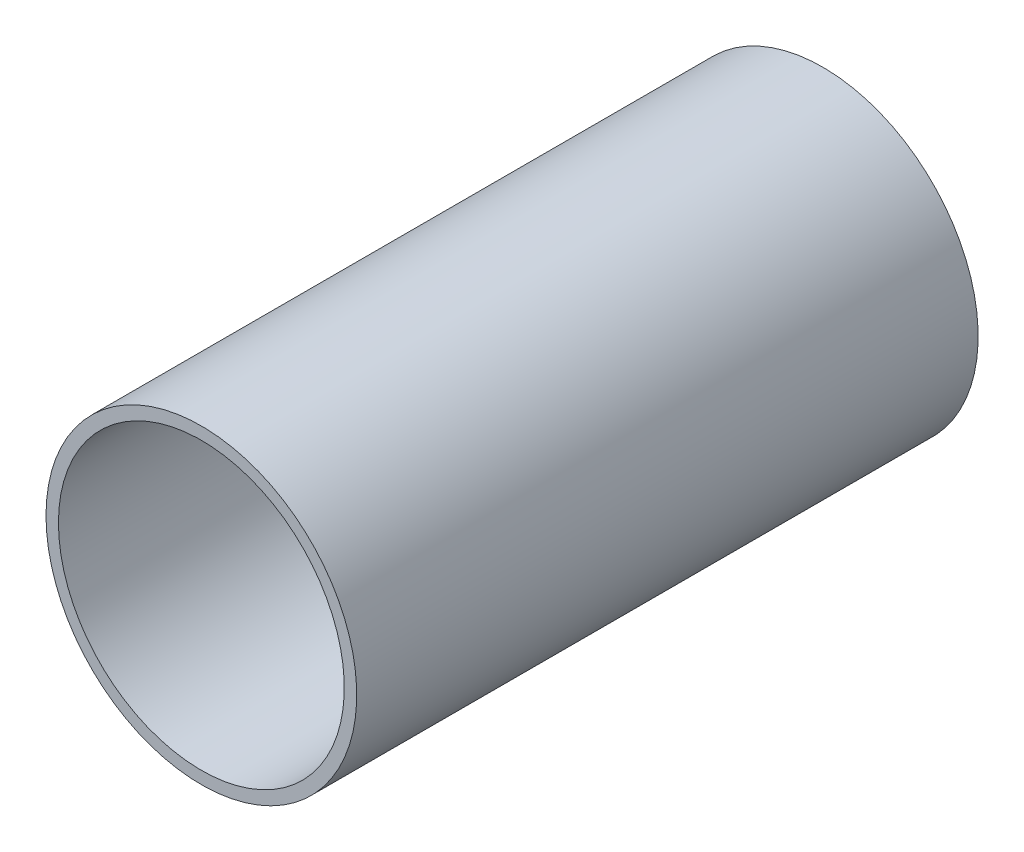
SolidWorks part; units mm, degrees
material "Plain Carbon Steel"
ref_plane "Front Plane" through (0, 0, 0) normal (0, 0, 1) x (1, 0, 0)
ref_plane "Top Plane" through (0, 0, 0) normal (0, 1, 0) x (1, 0, 0)
ref_plane "Right Plane" through (0, 0, 0) normal (1, 0, 0) x (0, 0, -1)
sketch "Sketch1" plane through (0, 0, 0) normal (0, 0, 1) x (1, 0, 0)
  circle A0 centre (0, 0) radius 38.1
  circle A1 centre (0, 0) radius 35.052
  dimension "D2" = 76.2
  dimension "D1" = 3.048
extrude "Boss-Extrude1" add sketch "Sketch1" along normal blind 152.4
